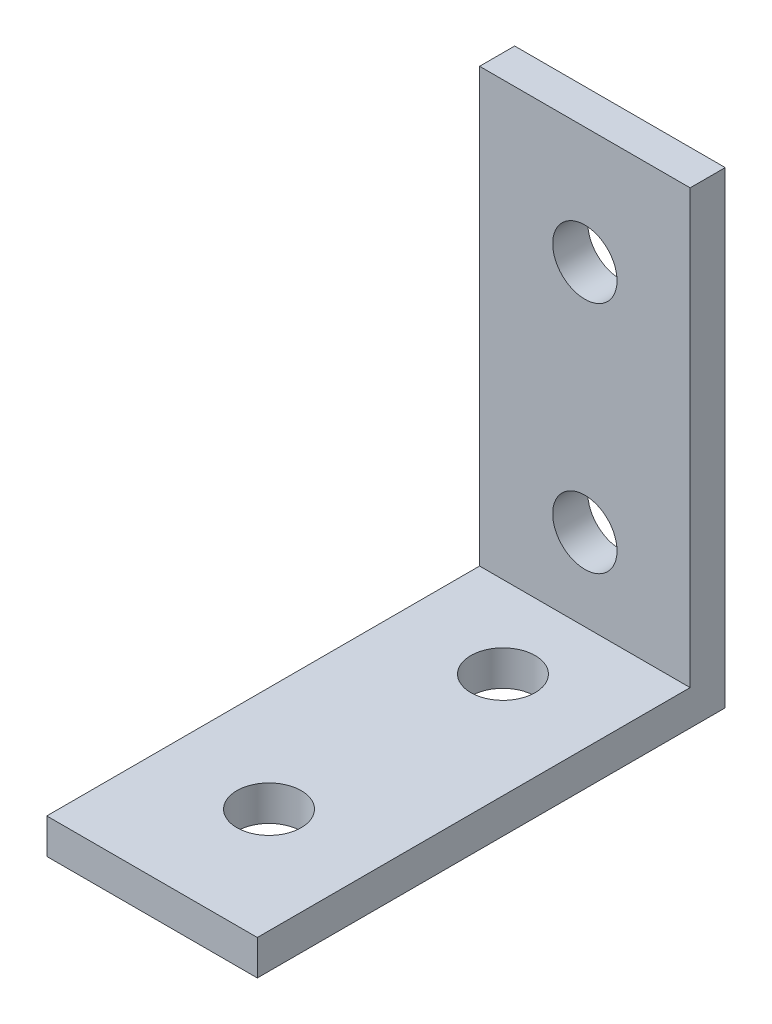
SolidWorks part; units mm, degrees
material "6061-T4 (SS)"
ref_plane "前视基准面" through (0, 0, 0) normal (0, 0, 1) x (1, 0, 0)
ref_plane "上视基准面" through (0, 0, 0) normal (0, 1, 0) x (1, 0, 0)
ref_plane "右视基准面" through (0, 0, 0) normal (1, 0, 0) x (0, 0, -1)
sketch "草图1" plane through (0, 0, 0) normal (0, 1, 0) x (1, 0, 0)
  line L0 (0, 20) -> (0, -20) construction
  line L1 (-9, 20) -> (9, 20)
  line L2 (-9, 20) -> (-9, -20)
  line L3 (-9, -20) -> (9, -20)
  line L4 (9, 20) -> (9, -20)
  line L5 (-9, 20) -> (9, -20) construction
  line L6 (-9, -20) -> (9, 20) construction
  circle A0 centre (0, -10) radius 2.75
  circle A1 centre (0, 10) radius 2.75
  point P0 (0, 0)
  dimension "D5" = 5.5
  dimension "D6" = 5.5
  dimension "D1" = 40
  dimension "D2" = 18
  dimension "D3" = 10
  dimension "D4" = 20
extrude "凸台-拉伸1" add sketch "草图1" along normal blind 3
ref_plane "基准面1" through (0, 3, 0) normal (0, 1, 0) x (1, 0, 0)
sketch "草图2" plane through (0, 3, 0) normal (0, 1, 0) x (1, 0, 0)
  line L0 (9, -20) -> (9, 20) construction
  line L1 (-9, 20) -> (9, 20)
  line L2 (-9, 20) -> (-9, 17)
  line L3 (-9, 17) -> (9, 17)
  line L4 (9, 20) -> (9, 17)
  dimension "D1" = 3
extrude "凸台-拉伸2" add sketch "草图2" along normal blind 37
ref_plane "基准面2" through (0, 0, -17) normal (0, 0, 1) x (1, 0, 0)
sketch "草图3" plane through (0, 0, -17) normal (0, 0, 1) x (1, 0, 0)
  line L0 (0, 40) -> (0, 30) construction
  line L1 (-9, 40) -> (9, 40) construction
  line L2 (0, 30) -> (0, 10) construction
  circle A0 centre (0, 30) radius 2.75
  circle A1 centre (0, 10) radius 2.75
  dimension "D1" = 5.5
  dimension "D2" = 5.5
  dimension "D3" = 10
  dimension "D4" = 20
extrude "切除-拉伸1" cut sketch "草图3" against normal blind 37
